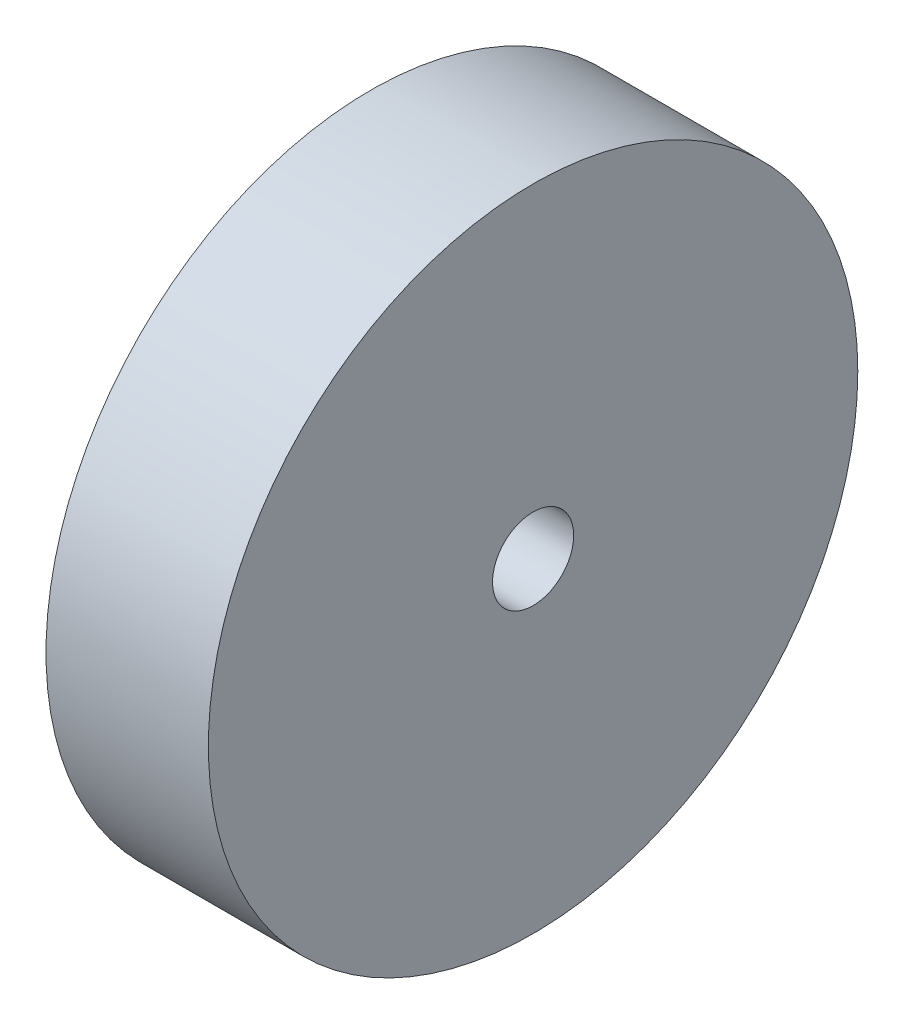
SolidWorks part; units mm, degrees
ref_plane "Front Plane" through (0, 0, 0) normal (0, 0, 1) x (1, 0, 0)
ref_plane "Top Plane" through (0, 0, 0) normal (0, 1, 0) x (1, 0, 0)
ref_plane "Right Plane" through (0, 0, 0) normal (1, 0, 0) x (0, 0, -1)
sketch "Sketch1" plane through (0, 0, 0) normal (1, 0, 0) x (0, 0, -1)
  circle A0 centre (0, 0) radius 25.4
  dimension "D1" = 50.8
extrude "Boss-Extrude2" add sketch "Sketch1" along normal blind 12.7
sketch "Sketch3" plane through (12.7, 0, 0) normal (1, 0, 0) x (0, 0, -1)
  circle A0 centre (0, 0) radius 3.175
  dimension "D1" = 6.35
extrude "Cut-Extrude1" cut sketch "Sketch3" against normal blind 6.35
